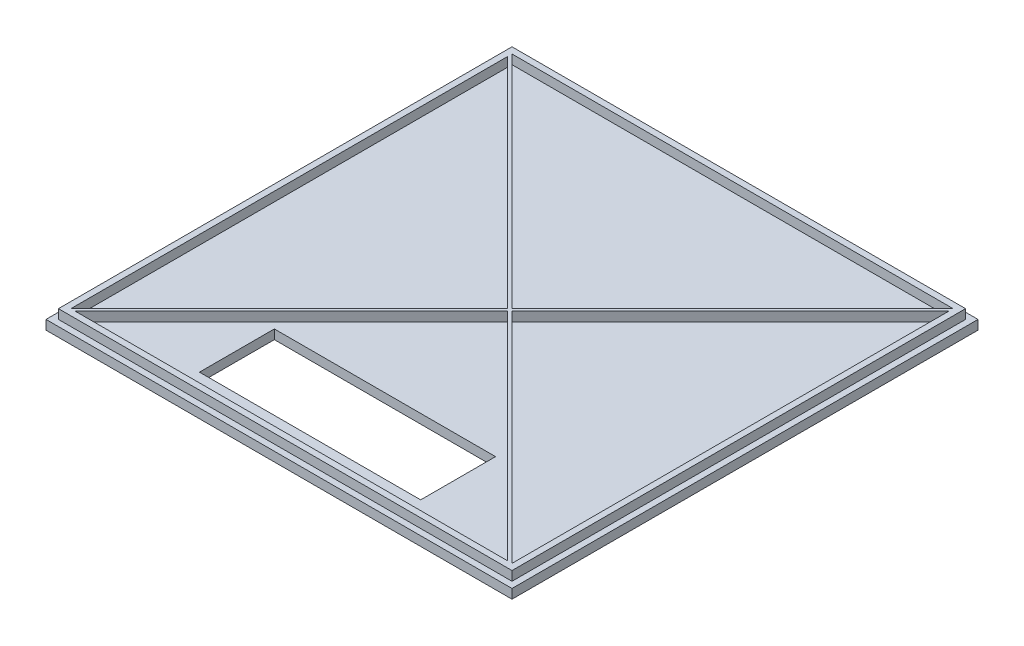
SolidWorks part; units mm, degrees
ref_plane "Front Plane" through (0, 0, 0) normal (0, 0, 1) x (1, 0, 0)
ref_plane "Top Plane" through (0, 0, 0) normal (0, 1, 0) x (1, 0, 0)
ref_plane "Right Plane" through (0, 0, 0) normal (1, 0, 0) x (0, 0, -1)
sketch "Sketch1" plane through (0, 0, 0) normal (0, 1, 0) x (1, 0, 0)
  line L1 (-75, 75) -> (75, 75)
  line L2 (-75, 75) -> (-75, -75)
  line L3 (-75, -75) -> (75, -75)
  line L4 (75, 75) -> (75, -75)
  line L5 (-75, 75) -> (75, -75) construction
  line L6 (-75, -75) -> (75, 75) construction
  point P0 (0, 0)
  dimension "D1" = 150
  dimension "D2" = 150
extrude "Boss-Extrude1" add sketch "Sketch1" against normal blind 3
sketch "Sketch2" plane through (0, 0, 0) normal (0, 1, 0) x (1, 0, 0)
  line L1 (-73, 73) -> (73, 73)
  line L2 (-73, 73) -> (-73, -73)
  line L3 (-73, -73) -> (73, -73)
  line L4 (73, 73) -> (73, -73)
  line L5 (-73, 73) -> (73, -73) construction
  line L6 (-73, -73) -> (73, 73) construction
  point P0 (0, 0)
  dimension "D1" = 146
  dimension "D2" = 146
extrude "Boss-Extrude2" add sketch "Sketch2" along normal blind 3
sketch "Sketch3" plane through (0, 0, 0) normal (0, 1, 0) x (1, 0, 0)
  line L1 (-71, 71) -> (71, 71)
  line L2 (-71, 71) -> (-71, -71)
  line L3 (-71, -71) -> (71, -71)
  line L4 (71, 71) -> (71, -71)
  line L5 (-71, 71) -> (71, -71) construction
  line L6 (-71, -71) -> (71, 71) construction
  point P0 (0, 0)
  dimension "D1" = 142
  dimension "D2" = 142
extrude "Cut-Extrude1" cut sketch "Sketch3" along normal up to surface (3 mm away) up to face at (0, 3, 0)
sketch "Sketch4" plane through (0, 0, 0) normal (0, 1, 0) x (1, 0, 0)
  line L0 (-71, 71) -> (71, -71)
  line L1 (-71, -71) -> (71, 71)
extrude "Extrude-Thin1" add sketch "Sketch4" along normal up to surface (3 mm away) thin
sketch "Sketch5" plane through (0, 0, 0) normal (0, 1, 0) x (1, 0, 0)
  line L0 (-75, 75) -> (-75, -75) construction
  line L1 (-35.6, -65) -> (35.6, -65)
  line L2 (-35.6, -65) -> (-35.6, -40.9)
  line L3 (-35.6, -40.9) -> (35.6, -40.9)
  line L4 (35.6, -65) -> (35.6, -40.9)
  line L5 (-35.6, -65) -> (35.6, -40.9) construction
  line L6 (-35.6, -40.9) -> (35.6, -65) construction
  line L7 (75, -75) -> (75, 75) construction
  line L8 (-75, -75) -> (75, -75) construction
  point P0 (0, -52.95)
  dimension "D1" = 71.2
  dimension "D2" = 24.1
  dimension "D3" = 39.4
  dimension "D4" = 39.4
  dimension "D5" = 10
extrude "Cut-Extrude5" cut sketch "Sketch5" against normal up to surface and the other way up to surface
